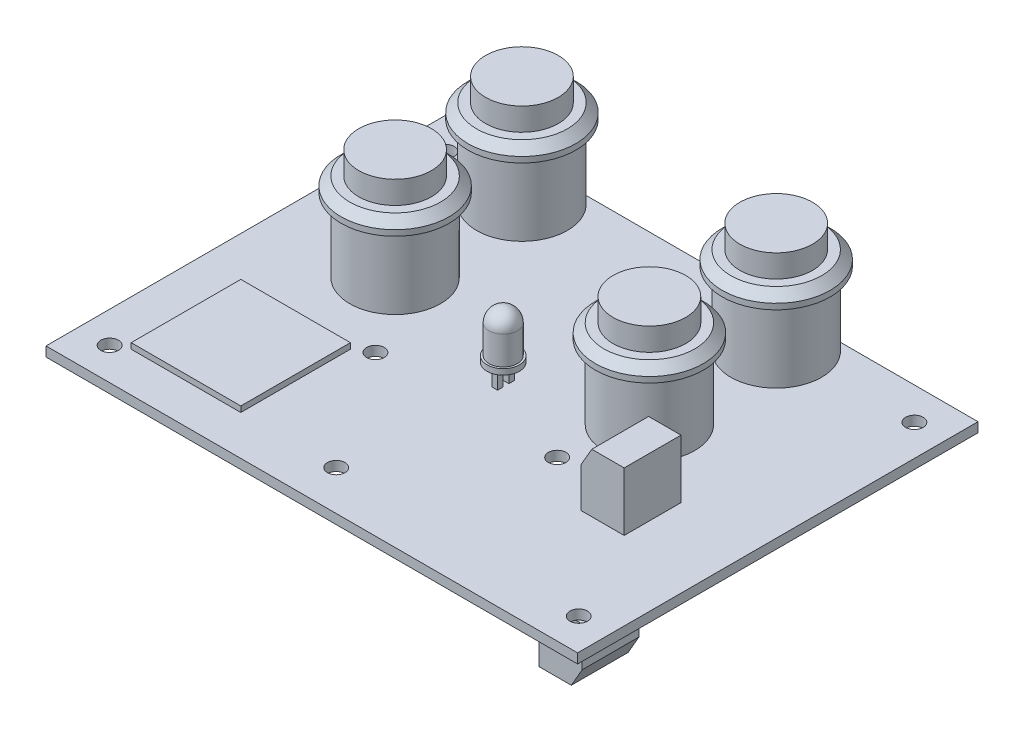
SolidWorks part; units mm, degrees
ref_plane "Alzado" through (0, 0, 0) normal (0, 0, 1) x (1, 0, 0)
ref_plane "Planta" through (0, 0, 0) normal (0, 1, 0) x (1, 0, 0)
ref_plane "Vista lateral" through (0, 0, 0) normal (1, 0, 0) x (0, 0, -1)
sketch "Croquis1" plane through (0, 0, 0) normal (0, 1, 0) x (1, 0, 0)
  line L1 (-46.8, 35.25) -> (46.8, 35.25)
  line L2 (-46.8, 35.25) -> (-46.8, -35.25)
  line L3 (-46.8, -35.25) -> (46.8, -35.25)
  line L4 (46.8, 35.25) -> (46.8, -35.25)
  line L5 (-46.8, 35.25) -> (46.8, -35.25) construction
  line L6 (-46.8, -35.25) -> (46.8, 35.25) construction
  point P0 (0, 0)
  dimension "D1" = 93.6
  dimension "D2" = 70.5
extrude "Saliente-Extruir1" add sketch "Croquis1" along normal blind 1.7
sketch "Croquis2" plane through (0, 1.7, 0) normal (0, 1, 0) x (1, 0, 0)
  line L0 (-46.8, -35.25) -> (46.8, -35.25) construction
  line L1 (-33.8, -13.95) -> (-14.5, -13.95)
  line L2 (-33.8, -13.95) -> (-33.8, -33.25)
  line L3 (-33.8, -33.25) -> (-14.5, -33.25)
  line L4 (-14.5, -13.95) -> (-14.5, -33.25)
  line L5 (-46.8, 35.25) -> (-46.8, -35.25) construction
  dimension "D1" = 19.3
  dimension "D2" = 2
  dimension "D3" = 13
extrude "Saliente-Extruir2" add sketch "Croquis2" along normal blind 1 from offset 5 separate body
sketch "Croquis3" plane through (0, 6.7, 0) normal (0, -1, 0) x (1, 0, 0)
  line L0 (-33.8, 23.6) -> (-14.5, 23.6) construction
  line L1 (-33.8, 13.95) -> (-33.8, 33.25) construction
  line L2 (-14.5, 33.25) -> (-14.5, 13.95) construction
  line L3 (-32.8, 25.1) -> (-32.8, 26.1)
  line L4 (-32.8, 23.1) -> (-31.8, 23.1)
  line L5 (-32.8, 23.1) -> (-32.8, 24.1)
  line L6 (-32.8, 24.1) -> (-31.8, 24.1)
  line L7 (-31.8, 23.1) -> (-31.8, 24.1)
  line L8 (-32.8, 25.1) -> (-31.8, 25.1)
  line L9 (-31.8, 25.1) -> (-31.8, 26.1)
  line L10 (-32.8, 26.1) -> (-31.8, 26.1)
  line L11 (-32.8, 23.1) -> (-32.8, 25.1) construction
  line L12 (-32.8, 24.1) -> (-32.8, 22.1) construction
  line L13 (-32.8, 21.1) -> (-31.8, 21.1)
  line L14 (-31.8, 22.1) -> (-31.8, 21.1)
  line L15 (-32.8, 22.1) -> (-31.8, 22.1)
  line L16 (-32.8, 22.1) -> (-32.8, 21.1)
  point P10 (-31.8, 23.6)
  dimension "D1" = 1
  dimension "D2" = 1
  dimension "D4" = 2
  dimension "D3" = 2
extrude "Saliente-Extruir3" add sketch "Croquis3" along normal up to surface (5 mm away) separate body up to face at (0, 1.7, 0)
sketch "Croquis4" plane through (0, 1.7, 0) normal (0, 1, 0) x (1, 0, 0)
  line L0 (-46.8, 35.25) -> (-46.8, -35.25) construction
  line L1 (46.8, 35.25) -> (-46.8, 35.25) construction
  circle A0 centre (-0.8, -0.75) radius 2.85
  dimension "D3" = 5.7
  dimension "D1" = 46
  dimension "D2" = 36
extrude "Saliente-Extruir4" add sketch "Croquis4" along normal blind 1 from offset 3.3 separate body
sketch "Croquis6" plane through (0, 6, 0) normal (0, 1, 0) x (1, 0, 0)
  line L0 (-0.8, 2.1) -> (-0.8, -3.6) construction
  circle A0 centre (-0.8, -0.75) radius 2.85 construction
ref_plane "Plano1" through (-0.8, 0, 0) normal (-1, 0, 0) x (0, 0, 1)
sketch "Croquis7" plane through (-0.8, 0, 0) normal (-1, 0, 0) x (0, 0, 1)
  line L0 (0.75, 6) -> (0.75, 13.5) construction
  line L1 (3.6, 6) -> (-2.1, 6) construction
  line L2 (0.75, 6) -> (-1.75, 6)
  line L3 (-1.75, 6) -> (-1.75, 11)
  line L4 (0.75, 6) -> (0.75, 13.5)
  arc A0 (-1.75, 11) -> (0.75, 13.5) centre (0.75, 11) cw
  dimension "D1" = 5
  dimension "D2" = 5
revolve "Revolución2" add sketch "Croquis7" angle 360 about L0
sketch "Croquis8" plane through (-0.8, 0, 0) normal (-1, 0, 0) x (0, 0, 1)
  line L0 (0.75, 5) -> (0.75, 13.5) construction
  line L1 (-2.1, 5) -> (3.6, 5) construction
  line L2 (-35.25, 1.7) -> (35.25, 1.7) construction
  line L3 (-0.75, 5) -> (0.25, 5)
  line L4 (-0.75, 5) -> (-0.75, 1.7)
  line L5 (-0.75, 1.7) -> (0.25, 1.7)
  line L6 (0.25, 5) -> (0.25, 1.7)
  line L8 (1.25, 5) -> (2.25, 5)
  line L9 (1.25, 5) -> (1.25, 1.7)
  line L10 (1.25, 1.7) -> (2.25, 1.7)
  line L11 (2.25, 5) -> (2.25, 1.7)
  arc A0 (3.25, 11) -> (-1.75, 11) centre (0.75, 11) ccw construction
  dimension "D1" = 1
  dimension "D2" = 1
extrude "Saliente-Extruir5" add sketch "Croquis8" along normal mid plane 1 separate body
sketch "Croquis10" plane through (0, 1.7, 0) normal (0, 1, 0) x (1, 0, 0)
  line L0 (-46.8, 35.25) -> (-46.8, -35.25) construction
  line L1 (26.9, -14.75) -> (34.5, -14.75)
  line L2 (26.9, -14.75) -> (26.9, -4.75)
  line L3 (26.9, -4.75) -> (34.5, -4.75)
  line L4 (34.5, -14.75) -> (34.5, -4.75)
  line L5 (26.9, -14.75) -> (34.5, -4.75) construction
  line L6 (26.9, -4.75) -> (34.5, -14.75) construction
  line L7 (46.8, 35.25) -> (-46.8, 35.25) construction
  point P0 (30.7, -9.75)
  dimension "D1" = 77.5
  dimension "D2" = 45
  dimension "D3" = 10
  dimension "D4" = 7.6
extrude "Saliente-Extruir6" add sketch "Croquis10" along normal blind 7 from offset 1.5 separate body
sketch "Croquis12" plane through (0, 0, 14.75) normal (0, 0, 1) x (1, 0, 0)
  line L0 (34.5, 10.2) -> (34.5, 13.5)
  line L1 (26.9, 10.2) -> (28.8053, 13.5)
  line L2 (28.8053, 13.5) -> (34.5, 13.5)
  line L3 (26.9, 10.2) -> (34.5, 10.2) construction
  line L4 (26.9, 10.2) -> (34.5, 10.2)
  dimension "D1" = 3.3
  dimension "D2" = 60
extrude "Saliente-Extruir7" add sketch "Croquis12" against normal up to surface (10 mm away) up to face at (30.7, 6.7, 4.75)
sketch "Croquis13" plane through (34.5, 0, 0) normal (1, 0, 0) x (0, 0, -1)
  line L0 (-14.75, 3.2) -> (-4.75, 3.2) construction
  line L1 (-12.75, 3.2) -> (-11.75, 3.2)
  line L2 (-12.75, 3.2) -> (-12.75, 1.7)
  line L3 (-12.75, 1.7) -> (-11.75, 1.7)
  line L4 (-11.75, 3.2) -> (-11.75, 1.7)
  line L5 (-35.25, 1.7) -> (35.25, 1.7) construction
  line L6 (-9.75, 3.2) -> (-9.75, 13.5) construction
  line L7 (-4.75, 13.5) -> (-14.75, 13.5) construction
  line L8 (-14.75, 13.5) -> (-14.75, 3.2) construction
  line L9 (-7.75, 3.2) -> (-7.75, 1.7)
  line L10 (-6.75, 1.7) -> (-7.75, 1.7)
  line L11 (-6.75, 3.2) -> (-6.75, 1.7)
  line L12 (-6.75, 3.2) -> (-7.75, 3.2)
  dimension "D1" = 1
  dimension "D2" = 2
extrude "Saliente-Extruir8" add sketch "Croquis13" against normal mid plane 1 from offset 3.8 separate body offset against normal yes
sketch "Croquis15" plane through (0, 0, 14.75) normal (0, 0, 1) x (1, 0, 0)
  line L0 (26.9, 3.2) -> (26.9, 10.2)
  line L1 (26.9, 10.2) -> (28.8053, 13.5)
  line L2 (28.8053, 13.5) -> (34.5, 13.5)
  line L3 (34.5, 13.5) -> (28.8053, 13.5) construction
  line L4 (34.5, 13.5) -> (34.5, 3.2)
  line L5 (34.5, 3.2) -> (26.9, 3.2)
  dimension "D1" = 10.3
  dimension "D2" = 5.6947
  dimension "D3" = 60
  dimension "D4" = 7.6
  dimension "D5" = 7
sketch "Croquis16" plane through (0, 0, 0) normal (0, -1, 0) x (1, 0, 0)
  line L0 (26.9, 14.75) -> (34.5, 14.75) construction
  line L1 (32, 27.25) -> (39.6, 27.25)
  line L2 (32, 27.25) -> (32, 17.25)
  line L3 (32, 17.25) -> (39.6, 17.25)
  line L4 (39.6, 27.25) -> (39.6, 17.25)
  line L5 (32, 27.25) -> (39.6, 17.25) construction
  line L6 (32, 17.25) -> (39.6, 27.25) construction
  line L7 (34.5, 14.75) -> (34.5, 4.75) construction
  line L9 (46.8, -35.25) -> (-46.8, -35.25) construction
  line L10 (46.8, 35.25) -> (46.8, -35.25) construction
  point P0 (35.8, 22.25)
  dimension "D1" = 11
  dimension "D2" = 57.5
extrude "Saliente-Extruir9" add sketch "Croquis16" along normal blind 1 from offset 1.5 separate body
sketch "Croquis18" plane through (0, 0, 27.25) normal (0, 0, 1) x (1, 0, 0)
  line L0 (39.6, -1.5) -> (39.6, -8.4918)
  line L1 (39.6, -8.4918) -> (37.69, -11.8)
  line L2 (37.69, -11.8) -> (32, -11.8)
  line L3 (32, -11.8) -> (32, -1.5)
  line L5 (32, -1.5) -> (39.6, -1.5)
  dimension "D1" = 10.3
  dimension "D2" = 60
  dimension "D3" = 5.69
extrude "Saliente-Extruir10" add sketch "Croquis18" against normal up to surface (10 mm away) up to face at (35.8, -2, 17.25)
sketch "Croquis20" plane through (39.6, 0, 0) normal (1, 0, 0) x (0, 0, -1)
  line L0 (-22.25, -1.5) -> (-22.25, -11.8) construction
  line L1 (-17.25, -1.5) -> (-27.25, -1.5) construction
  line L2 (-17.25, -11.8) -> (-27.25, -11.8) construction
  line L3 (-35.25, 0) -> (35.25, 0) construction
  line L4 (-25.25, -1.5) -> (-24.25, -1.5)
  line L5 (-25.25, -1.5) -> (-25.25, 0)
  line L6 (-25.25, 0) -> (-24.25, 0)
  line L7 (-24.25, -1.5) -> (-24.25, 0)
  line L8 (-27.25, -8.4918) -> (-27.25, -1.5) construction
  line L9 (-20.25, -1.5) -> (-20.25, 0)
  line L10 (-19.25, 0) -> (-20.25, 0)
  line L11 (-19.25, -1.5) -> (-19.25, 0)
  line L12 (-19.25, -1.5) -> (-20.25, -1.5)
  dimension "D1" = 2
  dimension "D2" = 1
extrude "Saliente-Extruir11" add sketch "Croquis20" against normal blind 1 from offset 3.8 separate body offset against normal yes
sketch "Croquis21" plane through (0, 1.7, 0) normal (0, 1, 0) x (1, 0, 0)
  line L1 (46.8, 35.25) -> (-46.8, 35.25) construction
  line L2 (46.8, -35.25) -> (46.8, 35.25) construction
  circle A0 centre (-22.3, 24.05) radius 8
  circle A1 centre (22.47, 24.05) radius 8
  circle A2 centre (-22.3, 1.72) radius 8
  circle A3 centre (22.47, 1.72) radius 8
  dimension "D3" = 16
  dimension "D1" = 24.33
  dimension "D2" = 11.2
  dimension "D4" = 44.77
  dimension "D5" = 22.33
extrude "Saliente-Extruir12" add sketch "Croquis21" along normal blind 13 from offset 4.2 separate body
sketch "Croquis23" plane through (0, 0, 0) normal (0, -1, 0) x (1, 0, 0)
  line L0 (-46.8, -35.25) -> (-46.8, 35.25) construction
  line L1 (-11.577, -17.382) -> (11.623, -17.382)
  line L2 (-11.577, -17.382) -> (-11.577, -25.582)
  line L3 (-11.577, -25.582) -> (11.623, -25.582)
  line L4 (11.623, -17.382) -> (11.623, -25.582)
  line L5 (-11.577, -17.382) -> (11.623, -25.582) construction
  line L6 (-11.577, -25.582) -> (11.623, -17.382) construction
  line L7 (46.8, -35.25) -> (-46.8, -35.25) construction
  point P0 (0.023, -21.482)
  dimension "D1" = 46.823
  dimension "D2" = 13.768
  dimension "D3" = 23.2
  dimension "D4" = 8.2
extrude "Saliente-Extruir13" add sketch "Croquis23" along normal blind 4 separate body
chamfer "Chaflán1" distance 1.5 angle 45 4 edges at (0.023, -4, -25.582) (-11.577, -4, -21.482) (0.023, -4, -17.382) (11.623, -4, -21.482)
sketch "Croquis24" plane through (0, 0, 0) normal (0, -1, 0) x (1, 0, 0)
  line L0 (-46.8, -35.25) -> (-46.8, 35.25) construction
  line L1 (-29.8, 32.25) -> (28.2, 32.25)
  line L2 (-29.8, 32.25) -> (-29.8, 3.25)
  line L3 (-29.8, 3.25) -> (28.2, 3.25)
  line L4 (28.2, 32.25) -> (28.2, 3.25)
  line L5 (46.8, -35.25) -> (-46.8, -35.25) construction
  dimension "D1" = 58
  dimension "D2" = 29
  dimension "D3" = 17
  dimension "D4" = 67.5
split line "Línea de partición1"
sketch "Croquis27" plane through (0, 0, 0) normal (0, -1, 0) x (1, 0, 0)
  line L0 (28.2, 32.25) -> (-29.8, 32.25) construction
  line L1 (-29.8, 32.25) -> (-29.8, 3.25) construction
  line L2 (-29.8, 3.25) -> (28.2, 3.25) construction
  line L3 (-0.8, 3.25) -> (-0.8, 32.25) construction
  line L4 (-46.8, -35.25) -> (-46.8, 35.25) construction
  line L5 (46.8, -35.25) -> (-46.8, -35.25) construction
  line L6 (46.8, 0) -> (-46.8, 0) construction
  line L7 (0, 35.25) -> (0, -35.25) construction
  circle A0 centre (-2.7, 28.25) radius 1.55
  circle A1 centre (-16.8, 7.25) radius 1.55
  circle A2 centre (15.2, 7.25) radius 1.55
  circle A3 centre (-41.3, -29.55) radius 1.55
  circle A4 centre (41.3, -29.55) radius 1.55
  circle A5 centre (41.3, 29.55) radius 1.55
  circle A6 centre (-41.3, 29.55) radius 1.55
  point P24 (0, 0)
  point P28 (0, 0)
  dimension "D1" = 3.1
  dimension "D2" = 4
  dimension "D3" = 27.1
  dimension "D4" = 4
  dimension "D5" = 13
  dimension "D6" = 5.5
  dimension "D7" = 5.7
extrude "Cortar-Extruir1" cut sketch "Croquis27" against normal through all
sketch "Croquis29" plane through (0, 18.9, 0) normal (0, 1, 0) x (1, 0, 0)
  circle A0 centre (-22.3, 24.05) radius 9.5
  circle A1 centre (22.47, 24.05) radius 9.5
  circle A2 centre (22.47, 24.05) radius 8 construction
  circle A3 centre (-22.3, 1.72) radius 9.5
  circle A4 centre (-22.3, 1.72) radius 8 construction
  circle A5 centre (22.47, 1.72) radius 9.5
  circle A6 centre (22.47, 1.72) radius 8 construction
  dimension "D1" = 19
extrude "Saliente-Extruir14" add sketch "Croquis29" along normal blind 2.5
chamfer "Chaflán2" distance 1.5 angle 45 1 edges at (-22.3, 21.4, -14.55)
chamfer "Chaflán3" distance 1.5 angle 45 1 edges at (-22.3, 21.4, 7.78)
chamfer "Chaflán4" distance 1.5 angle 45 1 edges at (22.47, 21.4, -14.55)
chamfer "Chaflán5" distance 1.5 angle 45 1 edges at (22.47, 21.4, 7.78)
sketch "Croquis30" plane through (0, 21.4, 0) normal (0, 1, 0) x (1, 0, 0)
  circle A0 centre (-22.3, 24.05) radius 6.4
  circle A1 centre (22.47, 24.05) radius 6.4
  circle A2 centre (-22.3, 1.72) radius 6.4
  circle A3 centre (22.47, 1.72) radius 6.4
  dimension "D1" = 12.8
extrude "Saliente-Extruir15" add sketch "Croquis30" along normal blind 4 separate body
